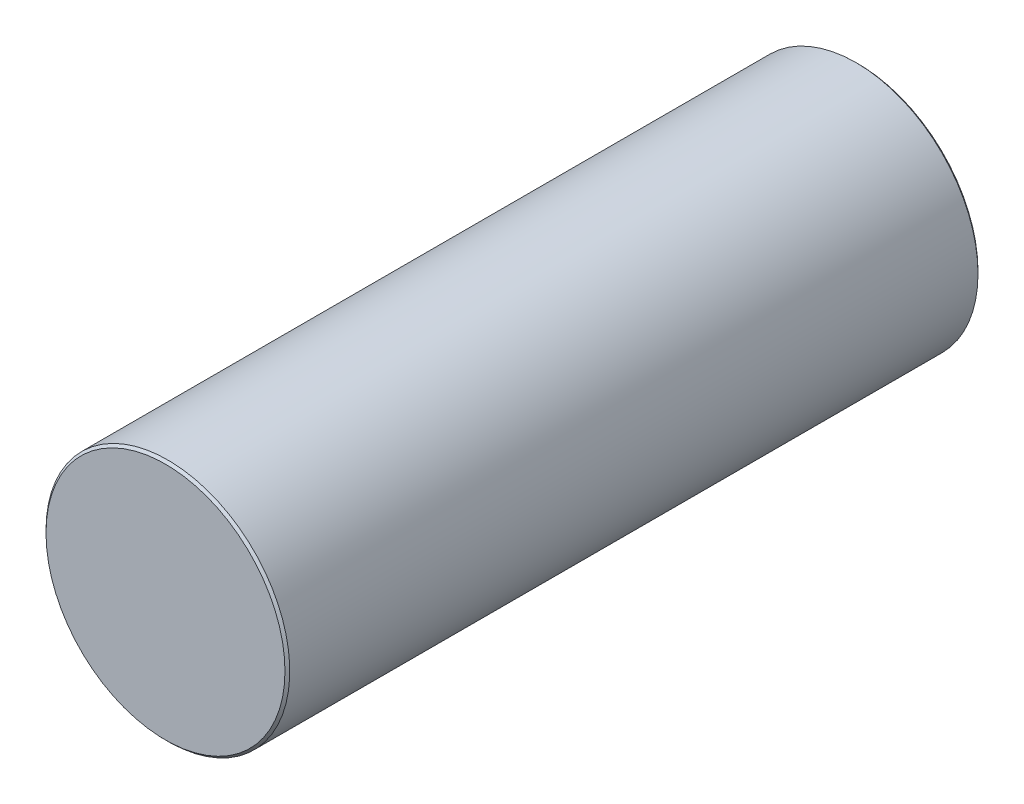
SolidWorks part; units mm, degrees
ref_plane "Front Plane" through (0, 0, 0) normal (0, 0, 1) x (1, 0, 0)
ref_plane "Top Plane" through (0, 0, 0) normal (0, 1, 0) x (1, 0, 0)
ref_plane "Right Plane" through (0, 0, 0) normal (1, 0, 0) x (0, 0, -1)
sketch "Sketch2" plane through (0, 0, 0) normal (0, 0, 1) x (1, 0, 0)
  circle A0 centre (0, 0) radius 2.55
  dimension "D1" = 5.1
extrude "Boss-Extrude1" add sketch "Sketch2" along normal blind 14.5
chamfer "Chamfer2" distance 0.05 angle 45 2 edges at (2.55, 0, 14.5) (2.55, 0, 0)
